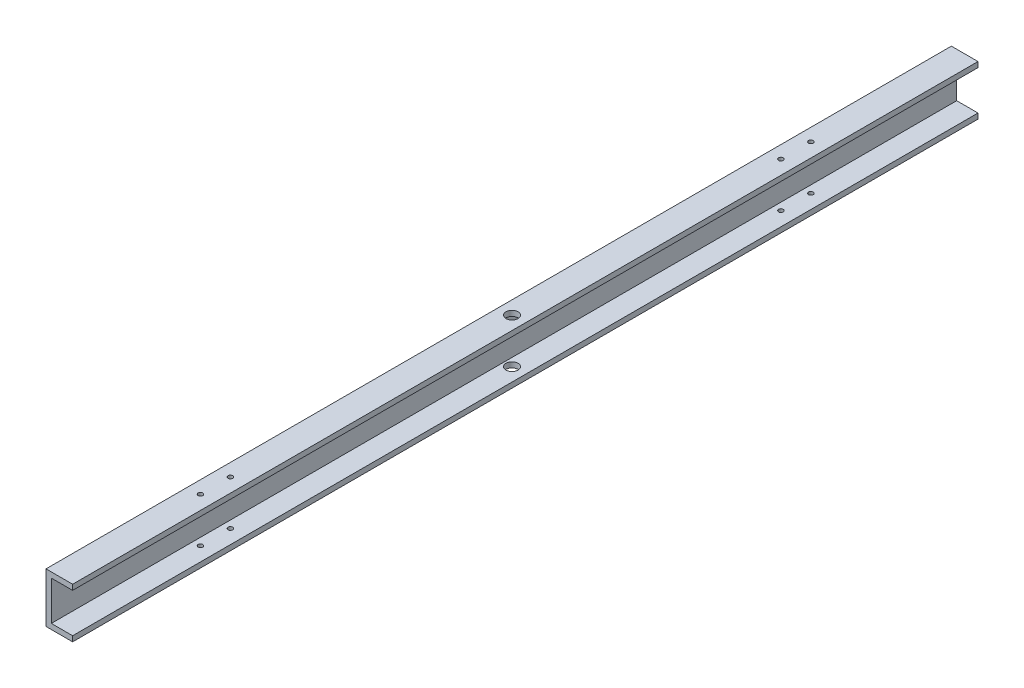
SolidWorks part; units mm, degrees
ref_plane "Front Plane" through (0, 0, 0) normal (0, 0, 1) x (1, 0, 0)
ref_plane "Top Plane" through (0, 0, 0) normal (0, 1, 0) x (1, 0, 0)
ref_plane "Right Plane" through (0, 0, 0) normal (1, 0, 0) x (0, 0, -1)
sketch "Sketch1" plane through (0, 0, -680) normal (0, 0, 1) x (1, 0, 0)
  line L0 (-440, 550) -> (-440, 625)
  line L1 (-440, 625) -> (-400, 625)
  line L2 (-400, 625) -> (-400, 617)
  line L3 (-400, 617) -> (-432, 617)
  line L4 (-432, 617) -> (-432, 558)
  line L5 (-432, 558) -> (-400, 558)
  line L6 (-400, 558) -> (-400, 550)
  line L7 (-400, 550) -> (-440, 550)
  line L9 (-400, 1025) -> (400, 1025) construction
  line L12 (-400, 950) -> (-400, -950) construction
  dimension "D1" = 40
  dimension "D2" = 75
  dimension "D3" = 8
  dimension "D4" = 8
  dimension "D5" = 475
extrude "Boss-Extrude1" add sketch "Sketch1" along normal up to surface (1360 mm away)
sketch "Sketch2" plane through (0, 625, 0) normal (0, 1, 0) x (1, 0, 0)
  line L0 (-400, -680) -> (-440, -680) construction
  line L1 (-440, -680) -> (-440, 680) construction
  line L2 (282.6355, 0) -> (-648.6147, 0) construction
  line L4 (-400, -680) -> (-400, 680) construction
  circle A0 centre (-421, -467) radius 3.5
  circle A1 centre (-421, -422) radius 3.5
  circle A2 centre (-420, 0) radius 9
  circle A5 centre (-421, 450) radius 3.5
  circle A6 centre (-421, 405) radius 3.5
  dimension "D2" = 7
  dimension "D6" = 18
  dimension "D8" = 7
  dimension "D1" = 45
  dimension "D3" = 213
  dimension "D4" = 19
  dimension "D5" = 20
  dimension "D7" = 45
  dimension "D9" = 1085
  dimension "D10" = 19
extrude "Cut-Extrude1" cut sketch "Sketch2" against normal through all
